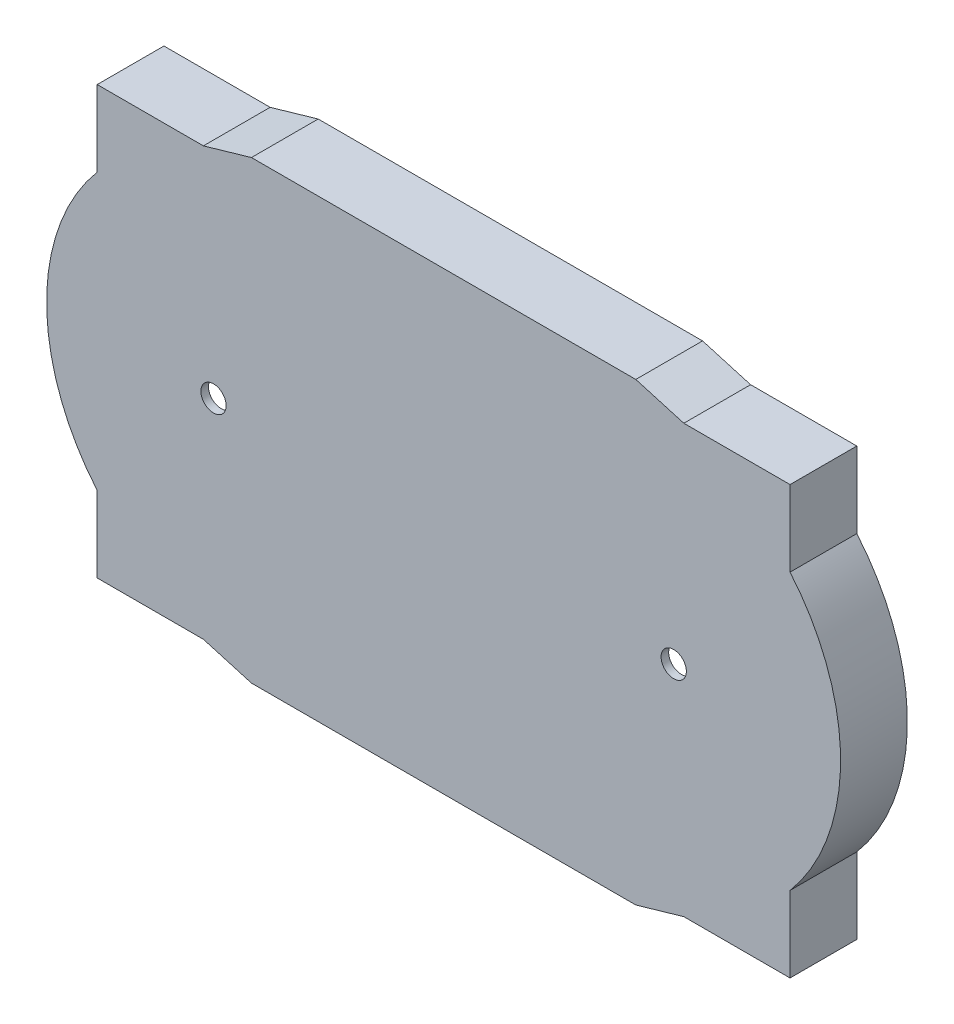
SolidWorks part; units mm, degrees
ref_plane "前视基准面" through (0, 0, 0) normal (0, 0, 1) x (1, 0, 0)
ref_plane "上视基准面" through (0, 0, 0) normal (0, 1, 0) x (1, 0, 0)
ref_plane "右视基准面" through (0, 0, 0) normal (1, 0, 0) x (0, 0, -1)
sketch "草图1" plane through (0, 0, 0) normal (0, 0, 1) x (1, 0, 0)
  line L0 (0, 72.4752) -> (0, -78.8585) construction
  line L1 (-78.5, 45) -> (78.5, 45)
  line L2 (-78.5, 45) -> (-78.5, -45)
  line L3 (-78.5, -45) -> (78.5, -45)
  line L4 (78.5, 45) -> (78.5, -45)
  line L5 (-109.7664, 0) -> (128.4587, 0) construction
  dimension "D1" = 157
  dimension "D2" = 90
extrude "凸台-拉伸1" add sketch "草图1" along normal blind 13.2
sketch "草图2" plane through (0, 0, 13.2) normal (0, 0, 1) x (1, 0, 0)
  line L0 (0, 55.2134) -> (0, -56.7825) construction
  line L1 (-93.0684, 0) -> (90.1263, 0) construction
  line L2 (-38, 45) -> (-47.5, 42.25)
  line L4 (78.5, 45) -> (-78.5, 45) construction
  line L5 (-47.5, 42.25) -> (-78.5, 42.25)
  line L7 (-78.5, 45) -> (-78.5, -45) construction
  line L8 (-78.5, 42.25) -> (-78.5, 45)
  line L9 (-78.5, 45) -> (-38, 45)
  line L10 (78.5, 45) -> (38, 45)
  line L11 (78.5, 42.25) -> (78.5, 45)
  line L12 (47.5, 42.25) -> (78.5, 42.25)
  line L13 (38, 45) -> (47.5, 42.25)
  line L14 (38, -45) -> (47.5, -42.25)
  line L15 (47.5, -42.25) -> (78.5, -42.25)
  line L16 (78.5, -42.25) -> (78.5, -45)
  line L17 (78.5, -45) -> (38, -45)
  line L18 (-78.5, -45) -> (-38, -45)
  line L19 (-78.5, -42.25) -> (-78.5, -45)
  line L20 (-47.5, -42.25) -> (-78.5, -42.25)
  line L21 (-38, -45) -> (-47.5, -42.25)
  dimension "D1" = 76
  dimension "D2" = 84.5
  dimension "D3" = 31
extrude "切除-拉伸1" cut sketch "草图2" against normal through all
sketch "草图3" plane through (0, 0, 13.2) normal (0, 0, 1) x (1, 0, 0)
  line L0 (-113.5829, 0) -> (96.2926, 0) construction
  line L1 (0, 67.6043) -> (0, -58.321) construction
  line L2 (-68.5, 42.25) -> (-68.5, 27.25)
  line L3 (-78.5, 42.25) -> (-47.5, 42.25) construction
  line L5 (-78.5, 42.25) -> (-78.5, -42.25) construction
  line L7 (-68.5, 42.25) -> (-78.5, 42.25)
  line L8 (-78.5, 42.25) -> (-78.5, -42.25)
  line L9 (-78.499, -6.4618) -> (-78.499, 15.1383) construction
  line L10 (-78.499, 6.4618) -> (-78.499, -15.1383) construction
  line L11 (-68.5, -42.25) -> (-78.5, -42.25)
  line L12 (-68.5, -42.25) -> (-68.5, -27.25)
  line L13 (78.499, 6.4618) -> (78.499, -15.1383) construction
  line L14 (78.499, -6.4618) -> (78.499, 15.1383) construction
  line L15 (68.5, -42.25) -> (68.5, -27.25)
  line L16 (68.5, -42.25) -> (78.5, -42.25)
  line L17 (78.5, 42.25) -> (78.5, -42.25)
  line L18 (68.5, 42.25) -> (78.5, 42.25)
  line L19 (68.5, 42.25) -> (68.5, 27.25)
  arc A0 (-68.5, 27.25) -> (-68.5, -27.25) centre (-36.3677, 0) ccw
  arc A1 (68.5, 27.25) -> (68.5, -27.25) centre (36.3677, 0) cw
  point P20 (-78.5, 0)
  point P33 (78.5, 0)
  dimension "D1" = 10
  dimension "D2" = 15
  dimension "D3" = 0.001
extrude "切除-拉伸2" cut sketch "草图3" against normal through all
shell "抽壳1" thickness 1.5
sketch "草图4" plane through (0, 0, 0) normal (0, 0, -1) x (-1, 0, 0)
  line L0 (-96.4027, 0) -> (94.6375, 0) construction
  line L1 (0, 51.8153) -> (0, -53.8033) construction
  circle A0 centre (-45.5, 0) radius 2.5
  circle A4 centre (45.5, 0) radius 2.5
  dimension "D1" = 5
extrude "切除-拉伸3" cut sketch "草图4" against normal blind 13.2
